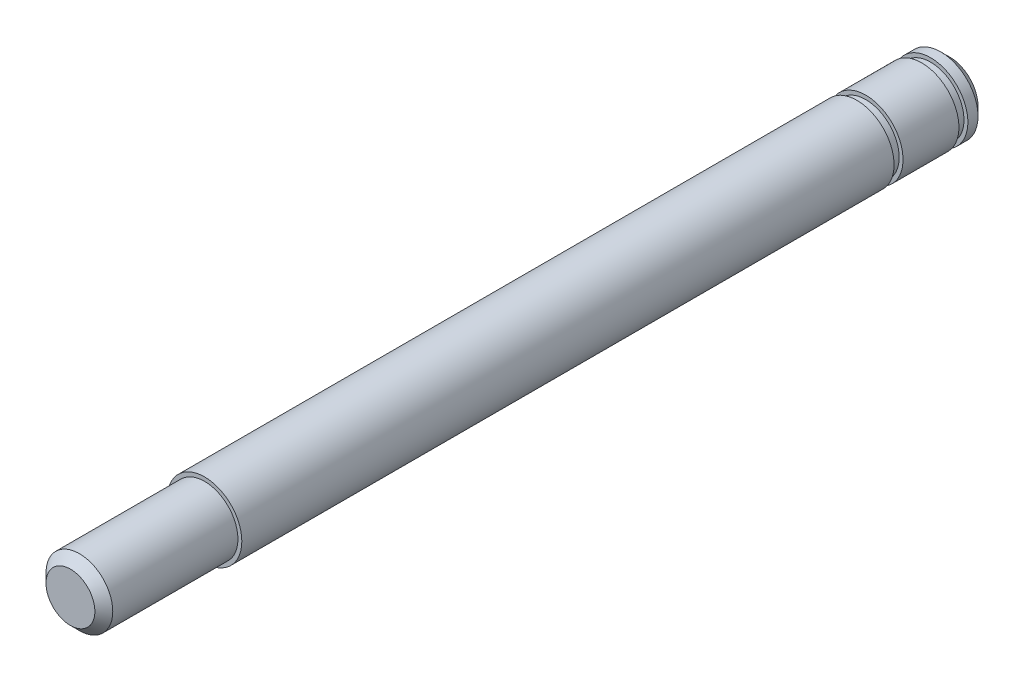
SolidWorks part; units mm, degrees
ref_plane "Front" through (0, 0, 0) normal (0, 0, 1) x (1, 0, 0)
ref_plane "Top" through (0, 0, 0) normal (0, 1, 0) x (1, 0, 0)
ref_plane "Right" through (0, 0, 0) normal (1, 0, 0) x (0, 0, -1)
sketch "Sketch1" plane through (0, 0, 0) normal (0, 0, 1) x (1, 0, 0)
  circle A0 centre (0, 0) radius 1.5875
  dimension "D1" = 3.175
extrude "Boss-Extrude1" add sketch "Sketch1" along normal mid plane 31.75
sketch "Sketch2" plane through (0, 0, 15.875) normal (0, 0, 1) x (1, 0, 0)
  circle A0 centre (0, 0) radius 1.4224
  dimension "D1" = 2.8448
extrude "Boss-Extrude2" add sketch "Sketch2" along normal blind 5.715
cosmetic thread "Cosmetic Thread1" parameters "D2"=2.0879
ref_plane "Plane1" through (0, 0, -15.0622) normal (0, 0, -1) x (-1, 0, 0)
sketch "Sketch3" plane through (0, 0, -15.0622) normal (0, 0, -1) x (-1, 0, 0)
  circle A0 centre (0, 0) radius 1.5875 construction
  circle A1 centre (0, 0) radius 1.4224 construction
  circle A2 centre (0, 0) radius 1.5875
  circle A3 centre (0, 0) radius 1.4224
extrude "Cut-Extrude1" cut sketch "Sketch3" against normal blind 0.381 contours A2 | A3
ref_plane "Plane2" through (0, 0, -12.3) normal (0, 0, -1) x (-1, 0, 0)
sketch "Sketch4" plane through (0, 0, -12.3) normal (0, 0, -1) x (-1, 0, 0)
  circle A0 centre (0, 0) radius 1.5875 construction
  circle A1 centre (0, 0) radius 1.5875 construction
  circle A2 centre (0, 0) radius 1.5875
  circle A3 centre (0, 0) radius 1.5875
  circle A4 centre (0, 0) radius 1.4224 construction
  circle A5 centre (0, 0) radius 1.4224
extrude "Cut-Extrude2" cut sketch "Sketch4" against normal blind 0.381 contours A2 | A5
chamfer "Chamfer1" distance 0.381 2 edges at (1.5875, 0, -15.875) (1.4224, 0, 21.59)
